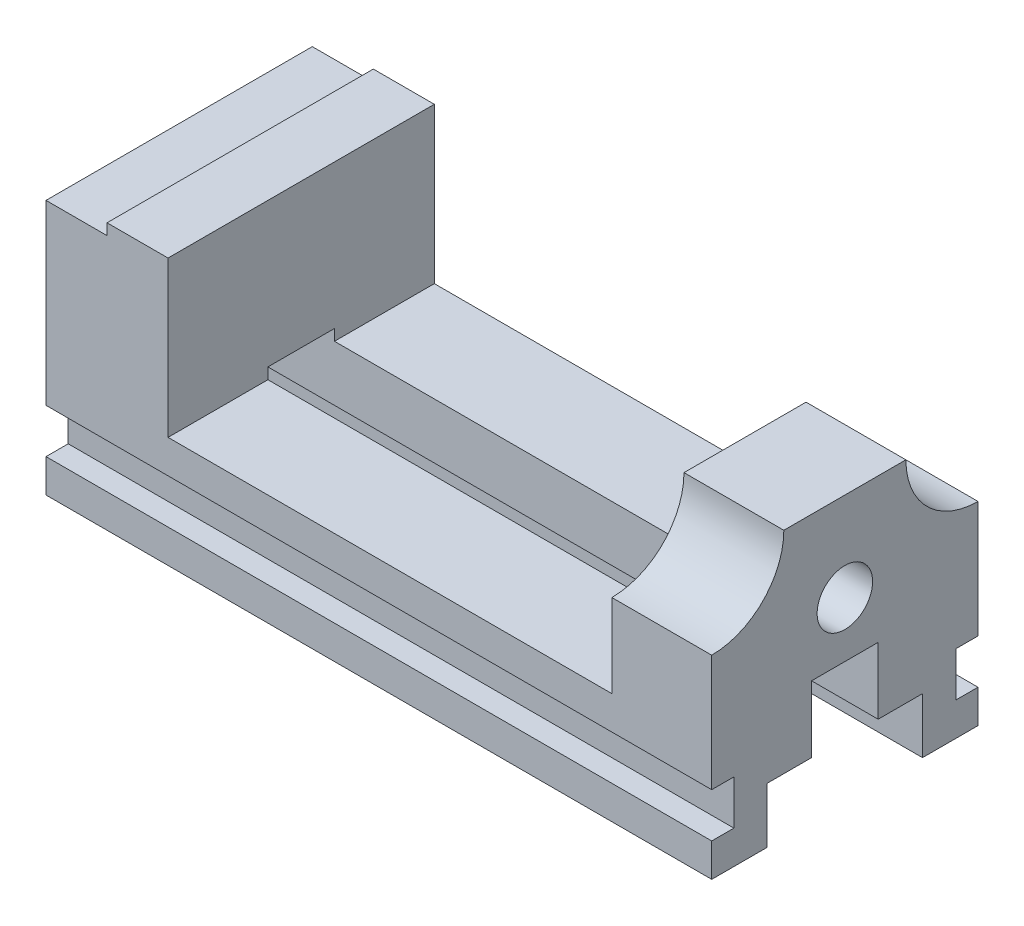
SolidWorks part; units mm, degrees
ref_plane "Front Plane" through (0, 0, 0) normal (0, 0, 1) x (1, 0, 0)
ref_plane "Top Plane" through (0, 0, 0) normal (0, 1, 0) x (1, 0, 0)
ref_plane "Right Plane" through (0, 0, 0) normal (1, 0, 0) x (0, 0, -1)
sketch "Sketch2" plane through (0, 0, 0) normal (0, 0, 1) x (1, 0, 0)
  line L0 (0, 73.025) -> (0, 0)
  line L1 (0, 0) -> (190.5, 0)
  line L2 (190.5, 0) -> (190.5, 76.2)
  line L3 (190.5, 76.2) -> (161.925, 76.2)
  line L4 (161.925, 76.2) -> (161.925, 31.75)
  line L5 (161.925, 31.75) -> (34.925, 31.75)
  line L6 (34.925, 31.75) -> (34.925, 76.2)
  line L7 (34.925, 76.2) -> (17.4625, 76.2)
  line L8 (34.925, 76.2) -> (17.4625, 76.2)
  line L9 (17.4625, 76.2) -> (17.4625, 73.025)
  line L10 (17.4625, 73.025) -> (0, 73.025)
  dimension "D1" = 76.2
  dimension "D2" = 73.025
  dimension "D3" = 190.5
  dimension "D4" = 127
  dimension "D5" = 31.75
  dimension "D6" = 76.2
  dimension "D7" = 34.925
  dimension "D8" = 17.4625
  dimension "D9" = 3.175
extrude "Extrude1" add sketch "Sketch2" against normal blind 76.2 contours L9 L10 L0 L1 L2 L3 L4 L5 L6 L7
ref_plane "Plane1" through (190.5, 0, 0) normal (1, 0, 0) x (0, 0, -1)
sketch "Sketch3" plane through (190.5, 0, 0) normal (1, 0, 0) x (0, 0, -1)
  line L0 (76.2, 76.2) -> (0, 76.2) construction
  line L1 (76.2, 76.2) -> (55.5625, 76.2)
  line L2 (0, 0) -> (0, 76.2) construction
  line L3 (0, 55.5625) -> (0, 76.2)
  line L4 (76.2, 0) -> (0, 0) construction
  line L5 (76.2, 0) -> (0, 0)
  line L6 (76.2, 0) -> (76.2, 76.2) construction
  line L7 (76.2, 55.5625) -> (76.2, 76.2)
  line L8 (20.6375, 76.2) -> (0, 76.2)
  arc A0 (0, 55.5625) -> (20.6375, 76.2) centre (0, 76.2) ccw
  arc A1 (55.5625, 76.2) -> (76.2, 55.5625) centre (76.2, 76.2) ccw
extrude "Extrude2" cut sketch "Sketch3" against normal up to vertex (28.575 mm away) contours L3 A0 L8 | L1 A1 L7 up to point (161.925, 76.2, 0)
sketch "Sketch4" plane through (190.5, 0, 0) normal (1, 0, 0) x (0, 0, -1)
  line L0 (38.1, 76.2) -> (38.1, 50.8) construction
  line L1 (55.5625, 76.2) -> (20.6375, 76.2) construction
  circle A0 centre (38.1, 50.8) radius 7.9375
  dimension "D1" = 25.4
extrude "Extrude3" cut sketch "Sketch4" against normal blind 76.2
sketch "Sketch5" plane through (190.5, 0, 0) normal (1, 0, 0) x (0, 0, -1)
  line L0 (38.1, 0) -> (38.1, 7.9375) construction
  line L1 (76.2, 0) -> (0, 0) construction
  line L2 (38.1, 15.875) -> (38.1, 25.4) construction
  line L3 (15.875, 15.875) -> (28.575, 15.875)
  line L4 (15.875, 15.875) -> (15.875, 0)
  line L5 (15.875, 0) -> (60.325, 0)
  line L6 (60.325, 15.875) -> (60.325, 0)
  line L7 (47.625, 15.875) -> (60.325, 15.875)
  line L10 (28.575, 34.925) -> (47.625, 34.925)
  line L11 (28.575, 34.925) -> (28.575, 15.875)
  line L13 (47.625, 34.925) -> (47.625, 15.875)
  dimension "D1" = 7.9375
  dimension "D2" = 44.45
  dimension "D3" = 9.525
  dimension "D4" = 19.05
extrude "Extrude4" cut sketch "Sketch5" against normal through all
sketch "Sketch6" plane through (190.5, 0, 0) normal (1, 0, 0) x (0, 0, -1)
  line L0 (0, 0) -> (0, 15.875) construction
  line L1 (0, 0) -> (0, 55.5625) construction
  line L2 (38.1, 34.925) -> (38.1, 3.1036) construction
  line L3 (-6.35, 9.525) -> (6.35, 9.525)
  line L4 (-6.35, 9.525) -> (-6.35, 22.225)
  line L5 (-6.35, 22.225) -> (6.35, 22.225)
  line L6 (6.35, 9.525) -> (6.35, 22.225)
  line L9 (47.625, 34.925) -> (28.575, 34.925) construction
  line L10 (69.85, 9.525) -> (69.85, 22.225)
  line L11 (82.55, 9.525) -> (69.85, 9.525)
  line L12 (82.55, 9.525) -> (82.55, 22.225)
  line L13 (82.55, 22.225) -> (69.85, 22.225)
  dimension "D1" = 15.875
  dimension "D2" = 12.7
  dimension "D3" = 12.7
extrude "Extrude5" cut sketch "Sketch6" against normal through all
